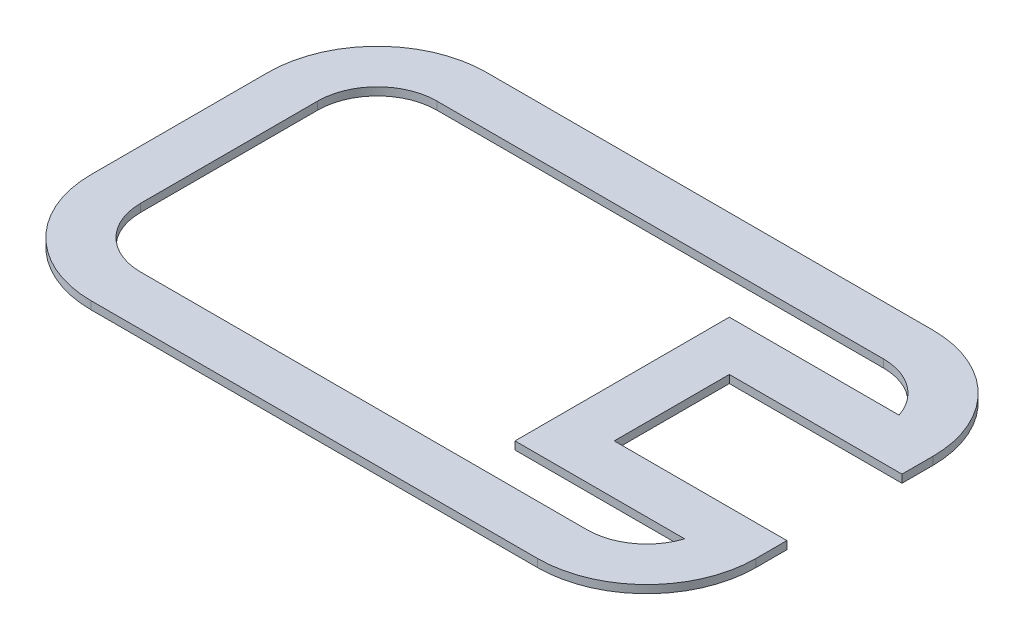
SolidWorks part; units mm, degrees
ref_plane "Front Plane" through (0, 0, 0) normal (0, 0, 1) x (1, 0, 0)
ref_plane "Top Plane" through (0, 0, 0) normal (0, 1, 0) x (1, 0, 0)
ref_plane "Right Plane" through (0, 0, 0) normal (1, 0, 0) x (0, 0, -1)
sketch "Sketch1" plane through (0, 0, 0) normal (0, 1, 0) x (1, 0, 0)
  line L0 (278.5285, -100.2791) -> (278.5285, -115.9091)
  line L1 (-1.5015, 28.3509) -> (223.5285, 28.3509)
  line L2 (-56.5015, -26.6491) -> (-56.5015, -115.9091)
  line L3 (-1.5015, -170.9091) -> (223.5285, -170.9091)
  line L4 (278.5285, -26.6491) -> (278.5285, -42.2791)
  line L5 (191.5285, -42.2791) -> (278.5285, -42.2791)
  line L6 (191.5285, -42.2791) -> (191.5285, -100.2791)
  line L7 (191.5285, -100.2791) -> (278.5285, -100.2791)
  line L8 (252.0277, -125.2791) -> (252.0277, -125.2791)
  line L9 (-1.5015, -145.9091) -> (223.5285, -145.9091)
  line L10 (-31.5015, -26.6491) -> (-31.5015, -115.9091)
  line L11 (-1.5015, 3.3509) -> (223.5285, 3.3509)
  line L12 (252.0277, -17.2791) -> (252.0277, -17.2791)
  line L13 (166.5285, -17.2791) -> (252.0277, -17.2791)
  line L14 (166.5285, -17.2791) -> (166.5285, -125.2791)
  line L15 (166.5285, -125.2791) -> (252.0277, -125.2791)
  arc A0 (-56.5015, -115.9091) -> (-1.5015, -170.9091) centre (-1.5015, -115.9091) ccw
  arc A1 (223.5285, -170.9091) -> (278.5285, -115.9091) centre (223.5285, -115.9091) ccw
  arc A2 (223.5285, 28.3509) -> (278.5285, -26.6491) centre (223.5285, -26.6491) cw
  arc A3 (-1.5015, 28.3509) -> (-56.5015, -26.6491) centre (-1.5015, -26.6491) ccw
  arc A4 (223.5285, -145.9091) -> (252.0277, -125.2791) centre (223.5285, -115.9091) ccw
  arc A5 (-31.5015, -115.9091) -> (-1.5015, -145.9091) centre (-1.5015, -115.9091) ccw
  arc A6 (-1.5015, 3.3509) -> (-31.5015, -26.6491) centre (-1.5015, -26.6491) ccw
  arc A7 (223.5285, 3.3509) -> (252.0277, -17.2791) centre (223.5285, -26.6491) cw
  point P6 (-56.5015, -170.9091)
  point P11 (278.5285, 28.3509)
  point P14 (-56.5015, 28.3509)
  dimension "D3" = 55
  dimension "D1" = 335.03
  dimension "D2" = 199.26
  dimension "D4" = 87
  dimension "D5" = 58
  dimension "D6" = 25
extrude "Boss-Extrude1" add sketch "Sketch1" along normal blind 4
